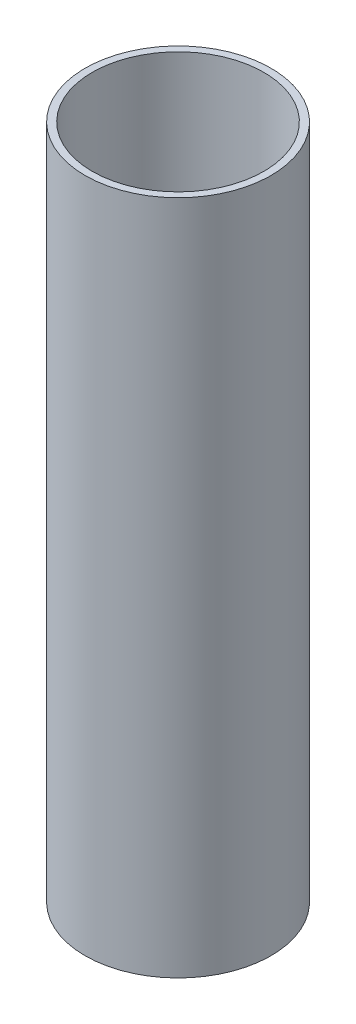
SolidWorks part; units mm, degrees
ref_plane "Front Plane" through (0, 0, 0) normal (0, 0, 1) x (1, 0, 0)
ref_plane "Top Plane" through (0, 0, 0) normal (0, 1, 0) x (1, 0, 0)
ref_plane "Right Plane" through (0, 0, 0) normal (1, 0, 0) x (0, 0, -1)
sketch "Sketch1" plane through (0, 0, 0) normal (0, 1, 0) x (1, 0, 0)
  circle A0 centre (0, 0) radius 41.275
  circle A1 centre (0, 0) radius 38.1
  dimension "D1" = 82.55
  dimension "D2" = 76.2
extrude "Boss-Extrude1" add sketch "Sketch1" along normal blind 300
